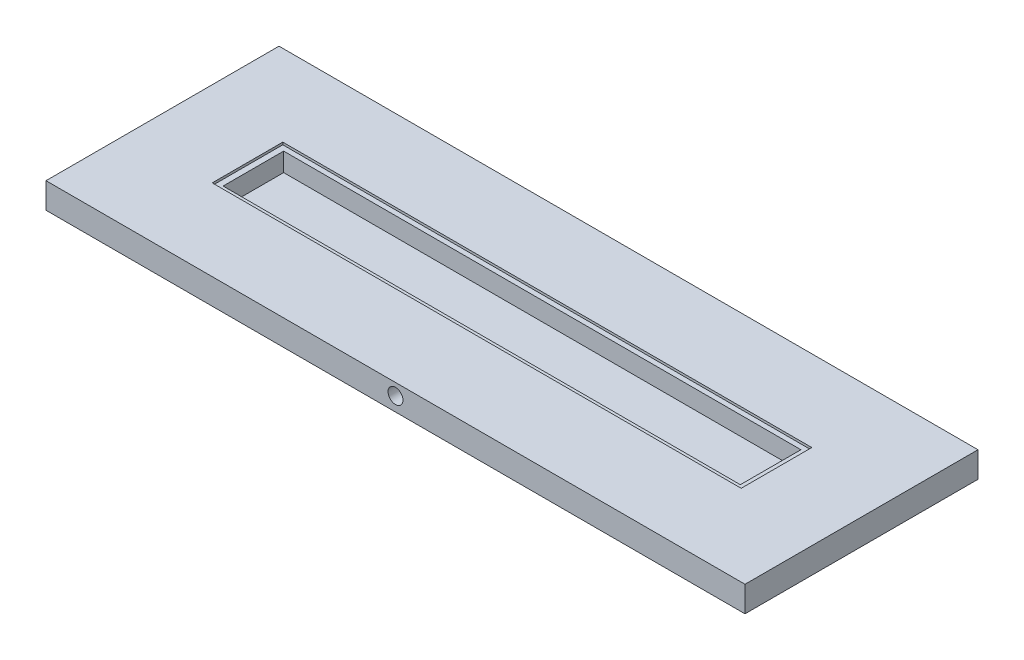
SolidWorks part; units mm, degrees
ref_plane "Front Plane" through (0, 0, 0) normal (0, 0, 1) x (1, 0, 0)
ref_plane "Top Plane" through (0, 0, 0) normal (0, 1, 0) x (1, 0, 0)
ref_plane "Right Plane" through (0, 0, 0) normal (1, 0, 0) x (0, 0, -1)
sketch "Sketch1" plane through (0, 0, 0) normal (0, 1, 0) x (1, 0, 0)
  line L1 (-750, 250) -> (750, 250)
  line L2 (-750, 250) -> (-750, -250)
  line L3 (-750, -250) -> (750, -250)
  line L4 (750, 250) -> (750, -250)
  line L5 (-750, 250) -> (750, -250) construction
  line L6 (-750, -250) -> (750, 250) construction
  point P0 (0, 0)
  dimension "D1" = 1500
  dimension "D2" = 500
sketch "Sketch19" plane through (0, 0, 0) normal (0, 1, 0) x (1, 0, 0)
  line L2 (-567.58, 75.76) -> (-567.58, -75.76)
  line L4 (-555, 65) -> (-555, -65)
  line L6 (-555, -65) -> (555, -65)
  line L8 (-567.58, -75.76) -> (567.58, -75.76)
  line L10 (-567.58, 75.76) -> (567.58, 75.76)
  line L12 (-555, 65) -> (555, 65)
  line L14 (0, 75.76) -> (0, -75.76) construction
  line L16 (555, 65) -> (555, -65)
  line L18 (567.58, 75.76) -> (567.58, -75.76)
  point P3 (-555, 0)
  dimension "D1" = 12.58
  dimension "D2" = 10.76
  dimension "D3" = 10.76
  dimension "D4" = 12.58
  dimension "D5" = 1135.16
  dimension "D6" = 151.52
extrude "Boss-Extrude2" add sketch "Sketch19" along normal blind 40 separate body
sketch "Sketch21" plane through (0, 0, 0) normal (0, 0, 1) x (1, 0, 0)
  line L0 (-567.58, 40) -> (567.58, 0) construction
  circle A0 centre (0, 20) radius 16
  dimension "D1" = 32
  dimension "D2" = 20
sketch "Sketch22" plane through (0, 0, 0) normal (0, 1, 0) x (1, 0, 0)
  line L1 (-567.58, 75.76) -> (567.58, 75.76)
  line L2 (-567.58, 75.76) -> (-567.58, -75.76)
  line L3 (-567.58, -75.76) -> (567.58, -75.76)
  line L4 (567.58, 75.76) -> (567.58, -75.76)
  line L5 (-567.58, 75.76) -> (567.58, -75.76) construction
  line L6 (-567.58, -75.76) -> (567.58, 75.76) construction
extrude "Boss-Extrude3" add sketch "Sketch22" against normal blind 10
sketch "Sketch23" plane through (0, 0, 0) normal (0, 1, 0) x (1, 0, 0)
  line L0 (-567.58, -75.76) -> (567.58, -75.76) construction
  line L1 (-750, 250) -> (750, 250)
  line L2 (-750, 250) -> (-750, -250)
  line L3 (-750, -250) -> (750, -250)
  line L4 (750, 250) -> (750, -250)
  line L5 (-567.58, 75.76) -> (-567.58, -75.76) construction
  line L6 (567.58, 75.76) -> (-567.58, 75.76) construction
  line L7 (567.58, -75.76) -> (567.58, 75.76) construction
  line L8 (-567.58, -75.76) -> (567.58, -75.76)
  line L9 (-567.58, 75.76) -> (-567.58, -75.76)
  line L10 (567.58, 75.76) -> (-567.58, 75.76)
  line L11 (567.58, -75.76) -> (567.58, 75.76)
extrude "Boss-Extrude4" add sketch "Sketch23" along normal offset from surface 5 and the other way up to surface (10 mm away) up to face at (0, 40, 0) offset beyond the face yes other way up to face at (0, -10, 0)
sketch "Sketch24" plane through (0, 0, 0) normal (0, 1, 0) x (1, 0, 0)
  line L1 (-50, -125.76) -> (50, -125.76)
  line L2 (-50, -125.76) -> (-50, -75.76)
  line L3 (-50, -75.76) -> (50, -75.76)
  line L4 (50, -125.76) -> (50, -75.76)
  line L8 (567.58, -75.76) -> (-567.58, -75.76) construction
  line L13 (-50, -165.76) -> (50, -165.76)
  line L14 (-50, -165.76) -> (-50, -215.76)
  line L15 (-50, -215.76) -> (50, -215.76)
  line L16 (50, -165.76) -> (50, -215.76)
  point P8 (0, -125.76)
  dimension "D1" = 50
  dimension "D2" = 40
  dimension "D5" = 50
  dimension "D6" = 100
extrude "Cut-Extrude5" cut sketch "Sketch21" along normal through all
sketch "Sketch25" plane through (0, 0, 0) normal (0, -1, 0) x (1, 0, 0)
  line L0 (376.7104, 80.76) -> (528.5967, 146.2835) construction
  line L1 (376.7104, 133.9838) -> (531.7281, 76.916) construction
  line L6 (-567.58, 75.76) -> (567.58, 75.76) construction
  line L8 (521.7058, 80.9826) -> (521.6427, 137.9826)
  line L9 (376.7104, 75.76) -> (520.9741, 75.76)
  line L10 (371.7104, 133.9838) -> (371.7104, 80.76)
  line L11 (520.6818, 138.8932) -> (376.6818, 138.9837)
  arc A0 (371.7104, 80.76) -> (376.7104, 75.76) centre (376.7104, 80.76) ccw
  arc A8 (520.9741, 75.76) -> (521.7058, 80.9826) centre (531.7281, 76.916) ccw
  arc A10 (376.6818, 138.9837) -> (371.7104, 133.9838) centre (376.7104, 133.9838) ccw
  arc A11 (521.6427, 137.9826) -> (520.6818, 138.8932) centre (528.5967, 146.2835) ccw
  point P2 (443.2788, 109.4775)
  dimension "D5" = 5
  dimension "D2" = 5
  dimension "D1" = 144
  dimension "D4" = 57
